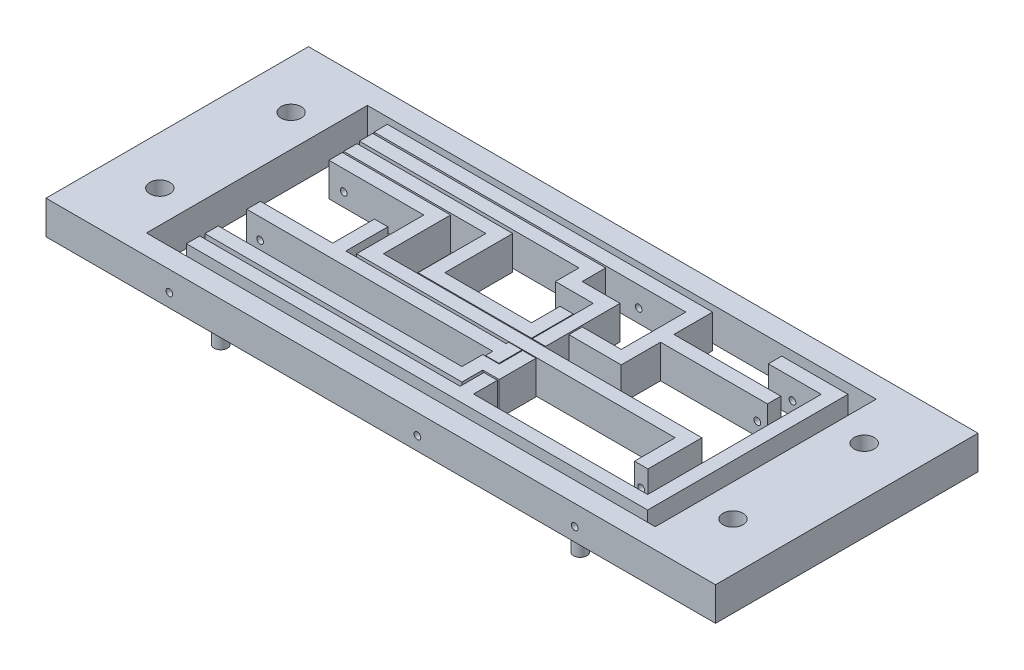
SolidWorks part; units mm, degrees
ref_plane "Front Plane" through (0, 0, 0) normal (0, 0, 1) x (1, 0, 0)
ref_plane "Top Plane" through (0, 0, 0) normal (0, 1, 0) x (1, 0, 0)
ref_plane "Right Plane" through (0, 0, 0) normal (1, 0, 0) x (0, 0, -1)
sketch "Sketch2" plane through (0, 0, 0) normal (0, 1, 0) x (1, 0, 0)
  line L0 (-54.356, 12.446) -> (-54.356, -12.446) construction
  line L1 (-63.5, -24.892) -> (63.5, -24.892)
  line L2 (-63.5, -24.892) -> (-63.5, 24.892)
  line L3 (-63.5, 24.892) -> (63.5, 24.892)
  line L4 (63.5, -24.892) -> (63.5, 24.892)
  line L5 (-63.5, -24.892) -> (63.5, 24.892) construction
  line L6 (-63.5, 24.892) -> (63.5, -24.892) construction
  line L7 (54.356, 12.446) -> (54.356, -12.446) construction
  line L8 (-54.356, 12.446) -> (54.356, 12.446) construction
  circle A0 centre (-54.356, 12.446) radius 1.905
  circle A1 centre (-54.356, -12.446) radius 1.905
  circle A2 centre (54.356, -12.446) radius 1.905
  circle A3 centre (54.356, 12.446) radius 1.905
  point P0 (0, 0)
  point P14 (-54.356, 0)
  point P15 (-63.5, 0)
  point P16 (54.356, 0)
  point P17 (63.5, 0)
  point P18 (0, 12.446)
  point P19 (0, 24.892)
  dimension "D3" = 3.81
  dimension "D1" = 127
  dimension "D2" = 49.784
  dimension "D4" = 24.892
  dimension "D5" = 108.712
  dimension "D7" = 24.892
extrude "Boss-Extrude1" add sketch "Sketch2" along normal blind 6.35
sketch "Sketch6" plane through (0, 0, 0) normal (0, 1, 0) x (1, 0, 0)
  line L0 (-63.5, 24.892) -> (-63.5, -24.892) construction
  line L1 (-48.26, 20.828) -> (48.26, 20.828)
  line L2 (-48.26, 20.828) -> (-48.26, -21.082)
  line L3 (-48.26, -21.082) -> (48.26, -21.082)
  line L4 (48.26, 20.828) -> (48.26, -21.082)
  line L5 (-63.5, -24.892) -> (63.5, -24.892) construction
  dimension "D1" = 41.91
  dimension "D2" = 96.52
  dimension "D3" = 15.24
  dimension "D4" = 3.81
extrude "Cut-Extrude4" cut sketch "Sketch6" along normal blind 6.35
sketch "Sketch14" plane through (0, 0, 0) normal (0, 1, 0) x (1, 0, 0)
  line L0 (-58.2351, 21.2843) -> (-58.2351, -20.686) construction
  line L1 (-23.2351, 21.8093) -> (-23.2351, -21.211) construction
  line L2 (-58.2351, -17.1856) -> (52.5615, -17.1856) construction
  line L3 (-58.2351, 17.7839) -> (52.5615, 17.7839) construction
  line L6 (11.7649, 22.3343) -> (11.7649, -20.686) construction
  line L7 (41.7649, 22.3343) -> (41.7649, -20.686) construction
  line L10 (-58.2351, 10.8144) -> (55.1015, 10.8144) construction
  line L11 (-58.2351, 3.8144) -> (52.5615, 3.8144) construction
  line L12 (-58.2351, -3.1856) -> (52.5615, -3.1856) construction
  line L13 (-58.2351, -10.1856) -> (52.5615, -10.1856) construction
  line L15 (-30.7351, 8.3144) -> (-25.7351, 8.3144)
  line L16 (-30.7351, 8.3144) -> (-30.7351, 13.3144)
  line L17 (-30.7351, 13.3144) -> (-25.7351, 13.3144)
  line L18 (-25.7351, 8.3144) -> (-25.7351, 13.3144)
  line L19 (-30.7351, 8.3144) -> (-25.7351, 13.3144) construction
  line L20 (-30.7351, 13.3144) -> (-25.7351, 8.3144) construction
  line L21 (-30.7351, 1.3144) -> (-25.7351, 1.3144)
  line L22 (-30.7351, 1.3144) -> (-30.7351, 6.3144)
  line L23 (-30.7351, 6.3144) -> (-25.7351, 6.3144)
  line L24 (-25.7351, 1.3144) -> (-25.7351, 6.3144)
  line L25 (-30.7351, 1.3144) -> (-25.7351, 6.3144) construction
  line L26 (-30.7351, 6.3144) -> (-25.7351, 1.3144) construction
  line L27 (4.2649, 15.2839) -> (9.2649, 15.2839)
  line L28 (4.2649, 15.2839) -> (4.2649, 20.2839)
  line L29 (4.2649, 20.2839) -> (9.2649, 20.2839)
  line L30 (9.2649, 15.2839) -> (9.2649, 20.2839)
  line L31 (4.2649, 15.2839) -> (9.2649, 20.2839) construction
  line L32 (4.2649, 20.2839) -> (9.2649, 15.2839) construction
  line L33 (4.2649, 8.3144) -> (9.2649, 8.3144)
  line L34 (4.2649, 8.3144) -> (4.2649, 13.3144)
  line L35 (4.2649, 13.3144) -> (9.2649, 13.3144)
  line L36 (9.2649, 8.3144) -> (9.2649, 13.3144)
  line L37 (4.2649, 8.3144) -> (9.2649, 13.3144) construction
  line L38 (4.2649, 13.3144) -> (9.2649, 8.3144) construction
  line L39 (4.2649, 1.3144) -> (9.2649, 1.3144)
  line L40 (4.2649, 1.3144) -> (4.2649, 6.3144)
  line L41 (4.2649, 6.3144) -> (9.2649, 6.3144)
  line L42 (9.2649, 1.3144) -> (9.2649, 6.3144)
  line L43 (4.2649, 1.3144) -> (9.2649, 6.3144) construction
  line L44 (4.2649, 6.3144) -> (9.2649, 1.3144) construction
  line L45 (4.2649, -5.6856) -> (9.2649, -5.6856)
  line L46 (4.2649, -5.6856) -> (4.2649, -0.6856)
  line L47 (4.2649, -0.6856) -> (9.2649, -0.6856)
  line L48 (9.2649, -5.6856) -> (9.2649, -0.6856)
  line L49 (4.2649, -5.6856) -> (9.2649, -0.6856) construction
  line L50 (4.2649, -0.6856) -> (9.2649, -5.6856) construction
  line L51 (4.2649, -12.6856) -> (9.2649, -12.6856)
  line L52 (4.2649, -12.6856) -> (4.2649, -7.6856)
  line L53 (4.2649, -7.6856) -> (9.2649, -7.6856)
  line L54 (9.2649, -12.6856) -> (9.2649, -7.6856)
  line L55 (4.2649, -12.6856) -> (9.2649, -7.6856) construction
  line L56 (4.2649, -7.6856) -> (9.2649, -12.6856) construction
  line L57 (34.2649, -19.6856) -> (39.2649, -19.6856)
  line L58 (34.2649, -19.6856) -> (34.2649, -14.6856)
  line L59 (34.2649, -14.6856) -> (39.2649, -14.6856)
  line L60 (39.2649, -19.6856) -> (39.2649, -14.6856)
  line L61 (34.2649, -19.6856) -> (39.2649, -14.6856) construction
  line L62 (34.2649, -14.6856) -> (39.2649, -19.6856) construction
  line L63 (34.2649, -12.6856) -> (39.2649, -12.6856)
  line L64 (34.2649, -12.6856) -> (34.2649, -7.6856)
  line L65 (34.2649, -7.6856) -> (39.2649, -7.6856)
  line L66 (39.2649, -12.6856) -> (39.2649, -7.6856)
  line L67 (34.2649, -12.6856) -> (39.2649, -7.6856) construction
  line L68 (34.2649, -7.6856) -> (39.2649, -12.6856) construction
  line L69 (34.2649, 15.2839) -> (39.2649, 15.2839)
  line L70 (34.2649, 15.2839) -> (34.2649, 20.2839)
  line L71 (34.2649, 20.2839) -> (39.2649, 20.2839)
  line L72 (39.2649, 15.2839) -> (39.2649, 20.2839)
  line L73 (34.2649, 15.2839) -> (39.2649, 20.2839) construction
  line L74 (34.2649, 20.2839) -> (39.2649, 15.2839) construction
  line L75 (34.2649, 8.3144) -> (39.2649, 8.3144)
  line L76 (34.2649, 8.3144) -> (34.2649, 13.3144)
  line L77 (34.2649, 13.3144) -> (39.2649, 13.3144)
  line L78 (39.2649, 8.3144) -> (39.2649, 13.3144)
  line L79 (34.2649, 8.3144) -> (39.2649, 13.3144) construction
  line L80 (34.2649, 13.3144) -> (39.2649, 8.3144) construction
  point P30 (-28.2351, 10.8144)
  point P35 (-28.2351, 3.8144)
  point P40 (6.7649, 10.8144)
  point P41 (6.7649, 17.7839)
  point P50 (6.7649, 3.8144)
  point P55 (6.7649, -3.1856)
  point P60 (6.7649, -10.1856)
  point P65 (36.7649, -10.1856)
  point P66 (36.7649, -17.1856)
  point P75 (36.7649, 17.7839)
  point P80 (36.7649, 10.8144)
  dimension "D1" = 35
  dimension "D2" = 35
  dimension "D3" = 30
  dimension "D6" = 7
  dimension "D7" = 7
  dimension "D8" = 7
  dimension "D9" = 7
  dimension "D10" = 5
  dimension "D11" = 5
  dimension "D12" = 5
  dimension "D13" = 5
  dimension "D14" = 5
  dimension "D15" = 5
sketch "Sketch3" plane through (0, 0, 0) normal (0, 1, 0) x (1, 0, 0)
  line L1 (-54.356, 12.446) -> (54.356, 12.446) construction
  line L2 (-54.356, 12.446) -> (-54.356, -12.446) construction
  line L3 (-54.356, -12.446) -> (54.356, -12.446) construction
  line L4 (54.356, 12.446) -> (54.356, -12.446) construction
  line B0 (6.1549, -15.6518) -> (6.1549, -11.7011)
  line B1 (3.6149, -13.1118) -> (-42.6072, -13.1118)
  line B2 (-42.6072, -13.1118) -> (-42.6072, -15.6518)
  line B3 (6.7296, -4.715) -> (6.7296, -9.1611)
  line B4 (9.2696, -11.7011) -> (9.2696, -4.715)
  line B5 (6.1549, -11.7011) -> (9.2696, -11.7011)
  line B6 (9.2696, -4.715) -> (6.7296, -4.715)
  line B7 (6.7296, -9.1611) -> (3.6149, -9.1611)
  line B8 (3.6149, -9.1611) -> (3.6149, -13.1118)
  line B9 (-42.6072, -15.6518) -> (6.1549, -15.6518)
  line B10 (6.6818, -19.0561) -> (44.7843, -19.0561)
  line B11 (44.7843, -19.0561) -> (44.7843, 18.9472)
  line B12 (44.7843, 18.9472) -> (32.2173, 18.9472)
  line B13 (32.2173, 18.9472) -> (32.2173, 16.4072)
  line B14 (32.2173, 16.4072) -> (42.2443, 16.4072)
  line B15 (42.2443, 16.4072) -> (42.2443, -16.5161)
  line B16 (9.2218, -16.5161) -> (42.2443, -16.5161)
  line B17 (9.2218, -16.5161) -> (9.2218, -12.005)
  line B18 (9.2218, -12.005) -> (6.6818, -12.005)
  line B19 (6.6818, -12.005) -> (6.6818, -16.5161)
  line B20 (6.6818, -16.5161) -> (-42.7073, -16.5161)
  line B21 (-42.7073, -16.5161) -> (-42.7073, -19.0561)
  line B22 (-42.7073, -19.0561) -> (6.6818, -19.0561)
  line B23 (4.0348, -9.0587) -> (6.5748, -9.0587)
  line B24 (6.5748, -9.0587) -> (6.5748, -4.6653)
  line B25 (-28.9193, -5.0763) -> (-28.9193, 2.8281)
  line B26 (-26.3793, 2.8281) -> (-26.3793, -2.0111)
  line B27 (-42.638, -5.0763) -> (-28.9193, -5.0763)
  line B28 (-28.9193, 2.8281) -> (-26.3793, 2.8281)
  line B29 (4.0348, -4.6653) -> (4.0348, -5.1391)
  line B30 (-42.638, -7.6791) -> (4.0348, -7.6791)
  line B31 (4.0348, -5.1391) -> (-26.3793, -5.1391)
  line B32 (6.5748, -4.6653) -> (4.0348, -4.6653)
  line B33 (-26.3793, -5.1391) -> (-26.3793, -2.0111)
  line B34 (4.0348, -9.0587) -> (4.0348, -7.6791)
  line B35 (-42.638, -5.0763) -> (-42.638, -7.6791)
  line B36 (38.0627, -12.2862) -> (35.5227, -12.2862)
  line B37 (-42.9063, 10.7127) -> (-22.3638, 10.7127)
  line B38 (-22.3638, 10.7127) -> (-22.3638, -2.0229)
  line B39 (-22.3638, -2.0229) -> (38.0627, -2.0399)
  line B40 (-37.8543, 8.1727) -> (-24.9038, 8.1727)
  line B41 (-24.9038, 8.1727) -> (-24.9038, -4.5622)
  line B42 (-24.9038, -4.5622) -> (35.5227, -4.5792)
  line B43 (35.5227, -4.5792) -> (35.5227, -12.2862)
  line B44 (38.0627, -2.0399) -> (38.0627, -12.2862)
  line B45 (-42.9063, 8.1727) -> (-37.8543, 8.1727)
  line B46 (-42.9063, 10.7127) -> (-42.9063, 8.1727)
  line B47 (-42.9641, 11.0238) -> (-42.9641, 13.5638)
  line B48 (-42.9641, 13.5638) -> (-13.4342, 13.5638)
  line B49 (-13.4342, 13.5638) -> (-13.4342, 0.6926)
  line B50 (-13.4342, 0.6926) -> (3.0133, 0.6926)
  line B51 (5.5533, -1.8474) -> (-15.9742, -1.8474)
  line B52 (-15.9742, -1.8474) -> (-15.9742, 11.0238)
  line B53 (-15.9742, 11.0238) -> (-42.9641, 11.0238)
  line B54 (5.5533, 6.0964) -> (5.5533, -1.8474)
  line B55 (3.0133, 0.6926) -> (3.0133, 6.0964)
  line B56 (3.0133, 6.0964) -> (5.5533, 6.0964)
  line B57 (15.8968, 2.2798) -> (8.5072, 2.2798)
  line B58 (18.4368, 12.2732) -> (38.7154, 12.2732)
  line B59 (38.7154, 12.2732) -> (38.7154, 9.7332)
  line B60 (18.4368, 2.2798) -> (15.8968, 2.2798)
  line B61 (38.7154, 9.7332) -> (18.4368, 9.7332)
  line B62 (18.4368, 9.7332) -> (18.4368, 2.2798)
  line B63 (2.4022, 19.6157) -> (-43.2584, 19.6157)
  line B64 (-43.2584, 19.6157) -> (-43.2584, 17.0757)
  line B65 (-43.2584, 17.0757) -> (-4.9898, 17.0757)
  line B66 (2.4022, 19.6157) -> (18.4368, 19.6157)
  line B67 (18.4368, 19.6157) -> (18.4368, 12.2732)
  line B68 (-4.9898, 17.0757) -> (15.8968, 17.0757)
  line B69 (15.8968, 17.0757) -> (15.8968, 4.8198)
  line B70 (8.5072, 2.2798) -> (8.5072, 4.8198)
  line B71 (8.5072, 4.8198) -> (15.8968, 4.8198)
  line B72 (-43.1538, 16.7355) -> (-43.1538, 14.1955)
  line B73 (-43.1538, 14.1955) -> (-11.02, 14.1955)
  line B74 (-11.02, 14.1955) -> (-1.4966, 14.1955)
  line B75 (-1.4966, 14.1955) -> (-1.4966, 9.7296)
  line B76 (1.0434, 16.7355) -> (-43.1538, 16.7355)
  line B77 (1.0434, 12.2696) -> (8.2221, 12.2696)
  line B78 (8.2221, 12.2696) -> (8.2221, 3.7987)
  line B79 (5.6959, 1.2587) -> (5.6959, -1.8478)
  line B80 (8.2359, -1.8478) -> (5.6959, -1.8478)
  line B81 (8.2359, 3.7987) -> (8.2359, -1.8478)
  line B82 (8.2221, 3.7987) -> (8.2359, 3.7987)
  line B83 (1.0434, 16.7355) -> (1.0434, 12.2696)
  line B84 (-1.4966, 9.7296) -> (5.6821, 9.7296)
  line B85 (5.6821, 9.7296) -> (5.6821, 1.2587)
  line B86 (5.6821, 1.2587) -> (5.6959, 1.2587)
sketch_block_instance "Block2-1"
sketch_block "Block2" parameters "D1"=2.54, "D2"=2.54, "D3"=5.3633, "D4"=2.54
sketch_block_instance "Block3-1"
sketch_block "Block3" parameters "D1"=2.54, "D2"=2.54, "D3"=2.54, "D4"=2.54
sketch_block_instance "Block5-1"
sketch_block "Block5" parameters "D1"=2.54, "D2"=2.54, "D3"=8.9277, "D4"=32.9541
sketch_block_instance "Block6-1"
sketch_block "Block6" parameters "D1"=2.54, "D2"=2.54, "D3"=2.54, "D4"=2.54, "D5"=2.54
sketch_block_instance "Block9-1"
sketch_block "Block9" parameters "D1"=2.54, "D2"=2.54, "D3"=2.54, "D4"=2.8098
sketch_block_instance "Block10-1"
sketch_block "Block10" parameters "D1"=2.54, "D2"=2.54, "D3"=2.54, "D4"=2.54, "D5"=2.54
sketch_block_instance "Block11-1"
sketch_block "Block11" parameters "D1"=2.54, "D2"=2.54, "D3"=2.54, "D4"=2.54, "D5"=6.8507, "D6"=4.4659
extrude "Boss-Extrude2" add sketch "Sketch3" along normal blind 6.35 separate body
sketch "Sketch15" plane through (0, 0, 7.6791) normal (0, 0, 1) x (1, 0, 0)
  line L1 (-42.638, 6.35) -> (-42.638, 0) construction
  line L2 (-42.638, 0) -> (4.0348, 0) construction
  circle A0 centre (-40.098, 2.54) radius 0.635
  dimension "D1" = 1.27
  dimension "D2" = 2.54
  dimension "D3" = 2.54
extrude "Cut-Extrude5" cut sketch "Sketch15" against normal blind 50.8 and the other way blind 25.4
sketch "Sketch16" plane through (0, 0, -12.2696) normal (0, 0, -1) x (-1, 0, 0)
  line L1 (-8.2221, 0) -> (-1.0434, 0) construction
  line L2 (-8.2221, 6.35) -> (-8.2221, 0) construction
  circle A0 centre (-6.9521, 2.54) radius 0.635
  dimension "D1" = 1.27
  dimension "D2" = 1.27
  dimension "D3" = 2.54
extrude "Cut-Extrude6" cut sketch "Sketch16" against normal blind 50.8 and the other way blind 50.8
sketch "Sketch17" plane through (-0.0006, 0, 2.0292) normal (0.0003, 0, -1) x (-1, 0, -0.0003)
  line L0 (-38.0633, 6.35) -> (-38.0633, 0) construction
  line L1 (-38.0633, 0) -> (22.3632, 0) construction
  circle A0 centre (-36.7933, 2.54) radius 0.635
  dimension "D1" = 1.27
  dimension "D2" = 1.27
  dimension "D3" = 2.54
extrude "Cut-Extrude7" cut sketch "Sketch17" against normal blind 50.8 and the other way blind 50.8
sketch "Sketch18" plane through (0, 0, 0) normal (0, -1, 0) x (1, 0, 0)
  line L9 (-63.5, 24.892) -> (63.5, 24.892) construction
  line L10 (48.26, -20.828) -> (-48.26, -20.828) construction
  circle A0 centre (-32.2508, 22.987) radius 1.27
  circle A1 centre (35.9339, 22.987) radius 1.27
  circle A2 centre (-32.2508, -22.733) radius 1.27
  circle A3 centre (35.9339, -22.733) radius 1.27
  dimension "D1" = 2.54
  dimension "D2" = 1.905
  dimension "D3" = 1.905
extrude "Boss-Extrude3" add sketch "Sketch18" along normal blind 3
